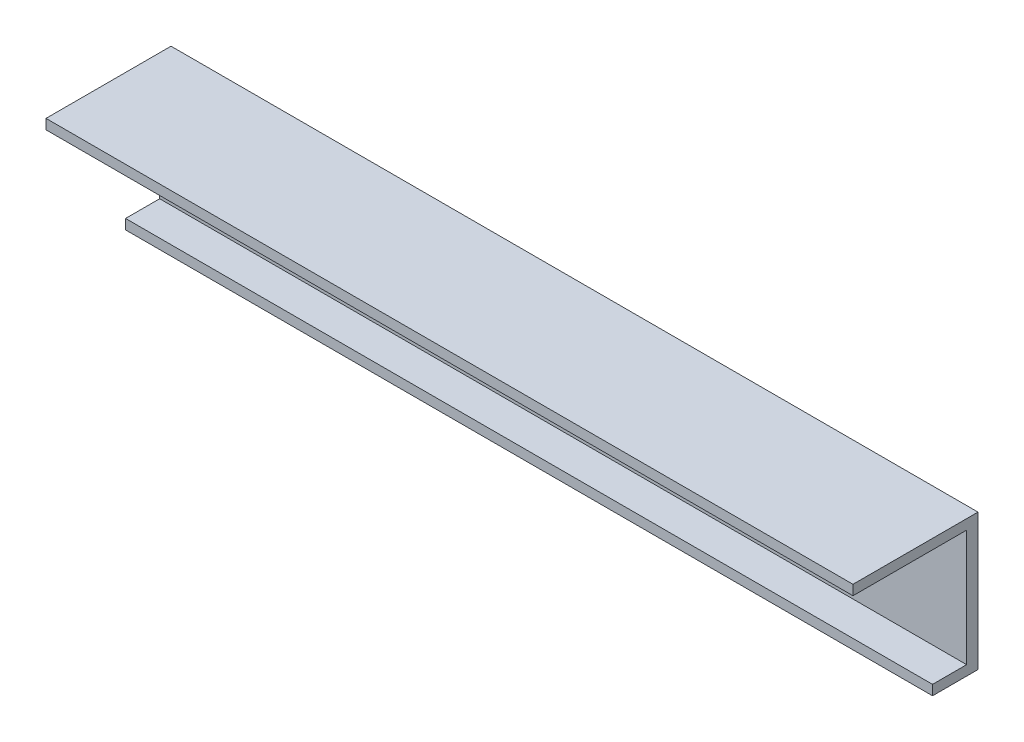
SolidWorks part; units mm, degrees
ref_plane "前视基准面" through (0, 0, 0) normal (0, 0, 1) x (1, 0, 0)
ref_plane "上视基准面" through (0, 0, 0) normal (0, 1, 0) x (1, 0, 0)
ref_plane "右视基准面" through (0, 0, 0) normal (1, 0, 0) x (0, 0, -1)
sketch "草图1" plane through (0, 0, 0) normal (0, 0, 1) x (1, 0, 0)
  line L1 (-112.3612, 24) -> (29.6388, 24)
  line L2 (-112.3612, 24) -> (-112.3612, 0)
  line L3 (-112.3612, 0) -> (29.6388, 0)
  line L4 (29.6388, 24) -> (29.6388, 0)
  dimension "D1" = 142
  dimension "D2" = 24
extrude "凸台-拉伸1" add sketch "草图1" along normal blind 22
sketch "草图2" plane through (29.6388, 0, 0) normal (1, 0, 0) x (0, 0, -1)
  line L0 (-22, 22.25) -> (-2, 22.25)
  line L1 (-22, 0) -> (-22, 24) construction
  line L2 (-2, 22.25) -> (-2, 1.75)
  line L3 (-2, 1.75) -> (-8, 1.75)
  line L4 (-8, 1.75) -> (-8, 0)
  line L5 (-22, 0) -> (0, 0) construction
  line L6 (-8, 0) -> (-22, 0)
  line L7 (-22, 0) -> (-22, 22.25)
  line L8 (-22, 24) -> (0, 24) construction
  line L9 (0, 0) -> (0, 24) construction
  dimension "D1" = 1.75
  dimension "D2" = 1.75
  dimension "D3" = 8
  dimension "D4" = 2
extrude "切除-拉伸1" cut sketch "草图2" against normal blind 142
